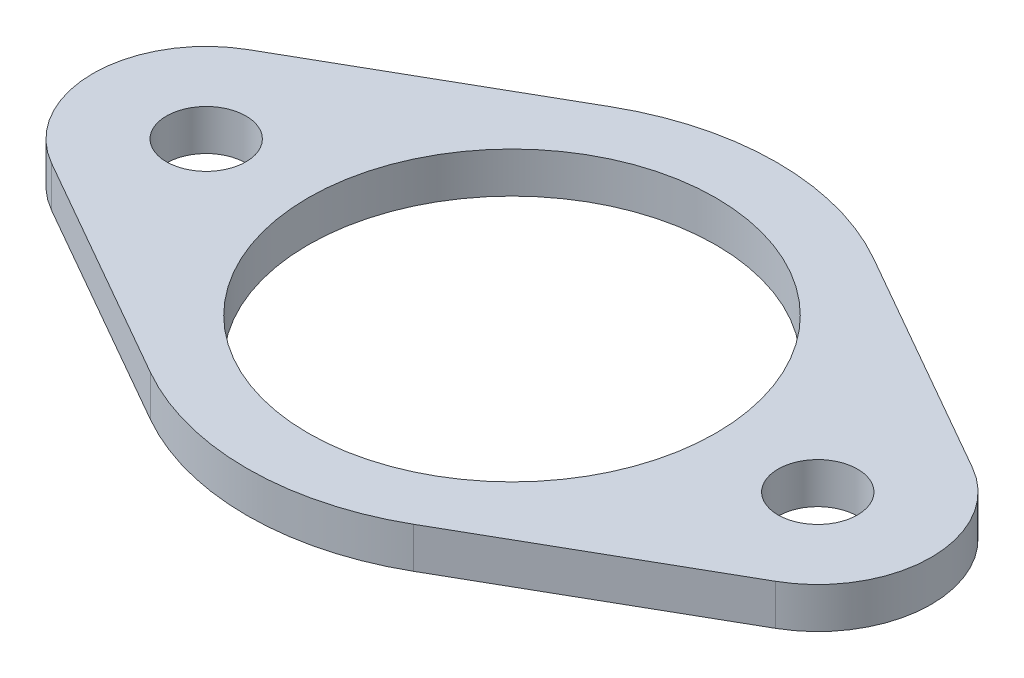
SolidWorks part; units mm, degrees
ref_plane "Front Plane" through (0, 0, 0) normal (0, 0, 1) x (1, 0, 0)
ref_plane "Top Plane" through (0, 0, 0) normal (0, 1, 0) x (1, 0, 0)
ref_plane "Right Plane" through (0, 0, 0) normal (1, 0, 0) x (0, 0, -1)
sketch "Sketch1" plane through (0, 0, 0) normal (0, 1, 0) x (1, 0, 0)
  line L0 (0, 0) -> (0, 6.5) construction
  line L1 (-8.8789, 2.4139) -> (-3.224, 5.6441)
  line L2 (-7.5, 0) -> (0, 0) construction
  line L3 (-8.8789, -2.4139) -> (-3.224, -5.6441)
  line L4 (8.8789, -2.4139) -> (3.224, -5.6441)
  line L5 (8.8789, 2.4139) -> (3.224, 5.6441)
  arc A1 (-8.8789, 2.4139) -> (-8.8789, -2.4139) centre (-7.5, 0) ccw
  arc A2 (8.8789, 2.4139) -> (8.8789, -2.4139) centre (7.5, 0) cw
  arc A3 (3.224, 5.6441) -> (-3.224, 5.6441) centre (0, 0) ccw
  arc A4 (-3.224, -5.6441) -> (3.224, -5.6441) centre (0, 0) ccw
  circle A5 centre (0, 0) radius 5
  circle A6 centre (-7.5, 0) radius 0.975
  circle A7 centre (7.5, 0) radius 0.975
  dimension "D2" = 5.56
  dimension "D3" = 10
  dimension "D4" = 1.95
  dimension "D5" = 1.95
  dimension "D1" = 7.5
extrude "Boss-Extrude1" add sketch "Sketch1" along normal blind 1
